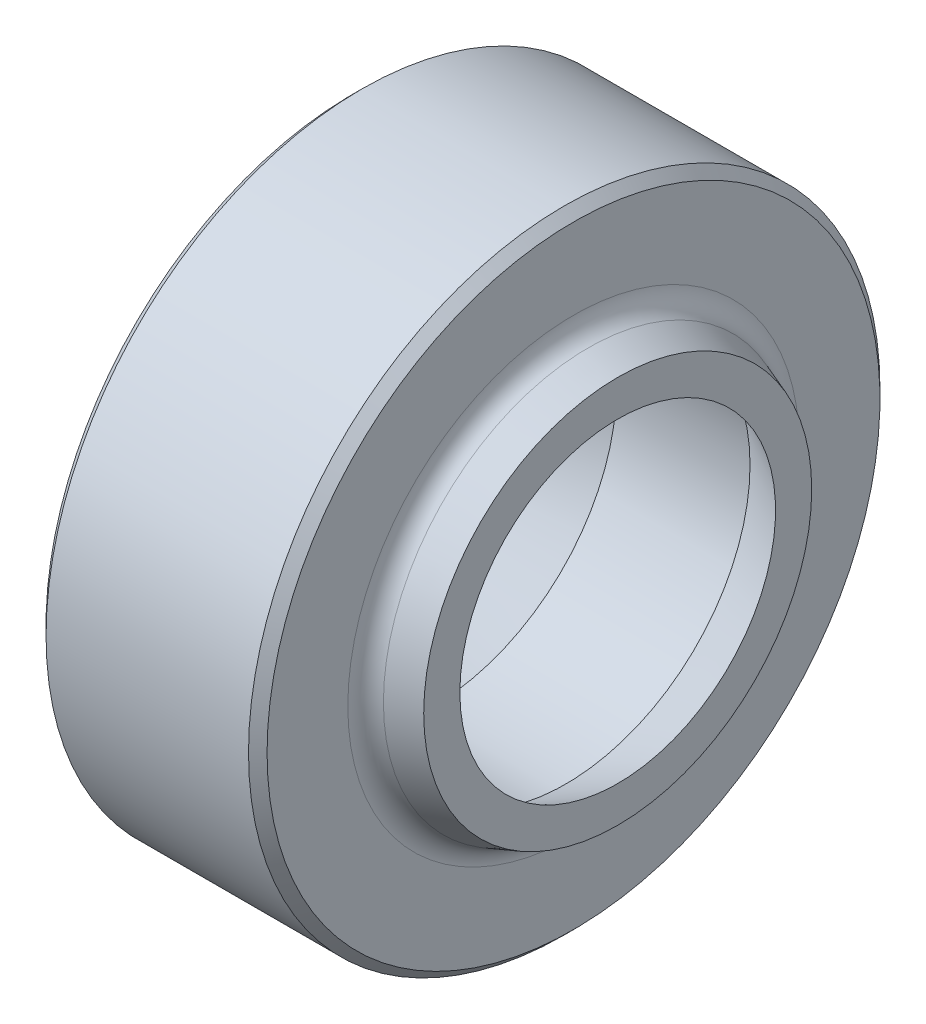
SolidWorks part; units mm, degrees
ref_plane "Přední rovina" through (0, 0, 0) normal (0, 0, 1) x (1, 0, 0)
ref_plane "Vrchní rovina" through (0, 0, 0) normal (0, 1, 0) x (1, 0, 0)
ref_plane "Pravá rovina" through (0, 0, 0) normal (1, 0, 0) x (0, 0, -1)
sketch "Skica1" plane through (0, 0, 0) normal (0, 0, 1) x (1, 0, 0)
  line L0 (0, 5) -> (3.5, 5)
  line L1 (3.5, 5) -> (3.5, 3.3271)
  line L2 (3.5, 3.3271) -> (4.2, 3.0724)
  line L3 (4.2, 3.0724) -> (4.2, 2.5)
  line L4 (4.2, 2.5) -> (3.3757, 2.92)
  line L5 (3.3757, 2.92) -> (1.26, 2.92)
  line L6 (1.26, 2.92) -> (0.42, 2.5)
  line L7 (0.42, 2.5) -> (0.168, 2.752)
  line L8 (0, 2.92) -> (0, 3.1772) construction
  line L9 (0.168, 3.2222) -> (2.3333, 3.8024)
  line L10 (2.3333, 3.8024) -> (0, 4.4276)
  line L11 (0, 4.4276) -> (0, 5)
  line L12 (0, 0) -> (4.2, 0) construction
  line L13 (3.5, 3.3271) -> (3.5, 3.0724) construction
  line L14 (3.5, 3.0724) -> (4.2, 3.0724) construction
  line L15 (3.3757, 2.92) -> (3.3757, 2.5) construction
  line L16 (3.3757, 2.5) -> (4.2, 2.5) construction
  line L17 (3.5, 5) -> (3.5, 4.1636) construction
  line L18 (3.5, 4.1636) -> (3.5, 3.3271) construction
  line L19 (3.3757, 2.5) -> (3.5, 3.3271) construction
  line L20 (2.3333, 3.8024) -> (3.5, 3.8024) construction
  line L21 (0, 3.8024) -> (1.1667, 3.8024) construction
  line L22 (1.1667, 3.8024) -> (2.3333, 3.8024) construction
  line L23 (0.168, 3.2222) -> (0.168, 2.752)
  line L24 (0.168, 3.2222) -> (0, 3.1772) construction
  line L25 (0, 2.92) -> (0.168, 2.752) construction
  dimension "D1" = 110
  dimension "B" = 4.2
  dimension "D3" = 10
  dimension "d" = 5
  dimension "D2" = 7
  dimension "L3" = 3.5
  dimension "D4" = 0.42
  dimension "D5" = 0.84
  dimension "D6" = 0.42
  dimension "D7" = 30
  dimension "D8" = 0.168
revolve "Otočit kolem osy1" add sketch "Skica1" angle 360 about L12
fillet "Zaoblit1" radius 0.294 1 edges at (2.3333, 0, 3.8024)
chamfer "Zkosit1" distance 0.147 angle 45 2 edges at (3.5, 0, 5) (0, 0, 5)
fillet "Zaoblit2" radius 0.3528 1 edges at (3.5, 0, 3.3271)
equation "\"D6@Skica1\" = \"D4@Skica1\""
equation "\"D5@Skica1\" = 2*\"D4@Skica1\""
equation "\"D4@Skica1\" = \"B@Skica1\" / 10"
equation "\"D1@Zaoblit1\" = \"D4@Skica1\" *0.7"
equation "\"D1@Zkosit1\" = \"D1@Zaoblit1\" * 0.5"
equation "\"D1@Zaoblit2\" = \"D1@Zaoblit1\" * 1.2"
equation "\"D8@Skica1\" = 0.4 * \"D4@Skica1\""
